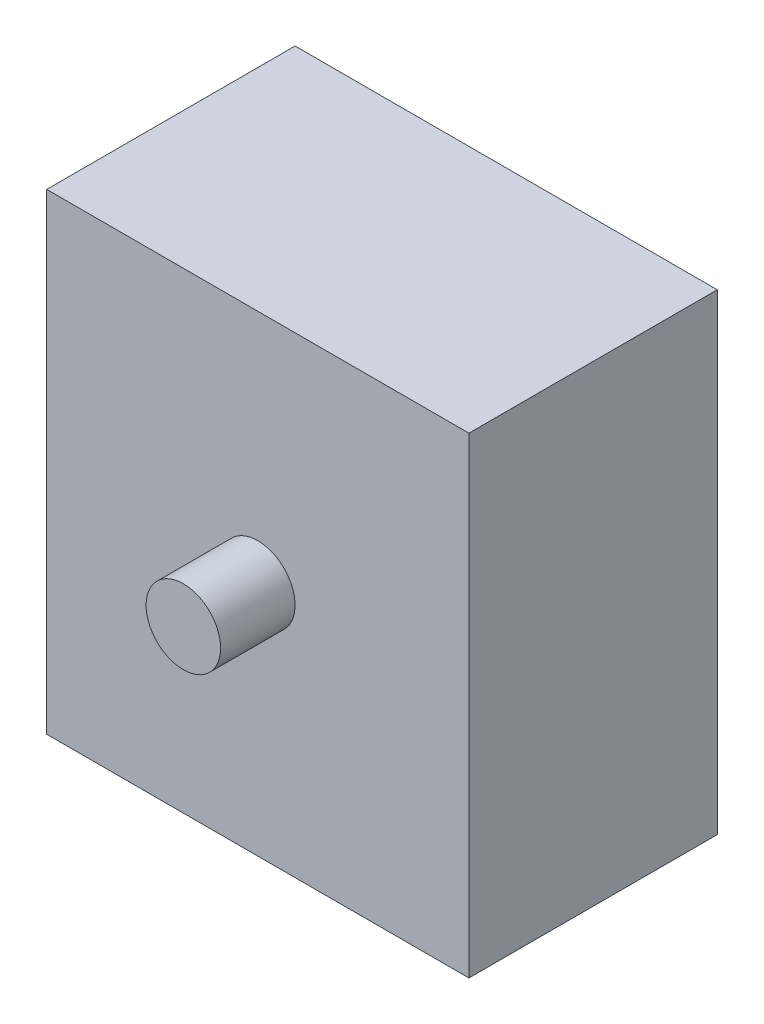
SolidWorks part; units mm, degrees
ref_plane "Top Plane" through (0, 0, 0) normal (0, 0, 1) x (1, 0, 0)
ref_plane "Front Plane" through (0, 0, 0) normal (0, 1, 0) x (1, 0, 0)
ref_plane "Right Plane" through (0, 0, 0) normal (1, 0, 0) x (0, 0, -1)
sketch "Sketch1" plane through (0, 0, 0) normal (0, 0, 1) x (1, 0, 0)
  line L0 (-8.5, 9.5) -> (8.5, -9.5) construction
  line L1 (-8.5, -9.5) -> (8.5, -9.5)
  line L2 (-8.5, -9.5) -> (-8.5, 9.5)
  line L3 (-8.5, 9.5) -> (8.5, 9.5)
  line L4 (8.5, -9.5) -> (8.5, 9.5)
  dimension "D1" = 17
  dimension "D2" = 19
extrude "Boss-Extrude1" add sketch "Sketch1" against normal blind 10 contours L3 L4 L1 L2
sketch "Sketch3" plane through (0, 0, 0) normal (0, 0, 1) x (1, 0, 0)
  circle A0 centre (0, 0) radius 1.5
  dimension "D1" = 3
extrude "Boss-Extrude2" add sketch "Sketch3" along normal blind 3
sketch "Sketch4" plane through (0, 0, 0) normal (0, 0, 1) x (1, 0, 0)
  line L0 (0, 0) -> (0, 1.5) construction
  line L1 (0, 9.5) -> (0, 4.5) construction
  line L2 (-8.5, 9.5) -> (8.5, 9.5) construction
  line L3 (0, 4.5) -> (-12.75, 4.5) construction
  line L4 (-8.5, -9.5) -> (-8.5, 9.5) construction
  line L5 (0, 0) -> (0, -4.5) construction
  line L6 (0, 13) -> (-12.75, 13) construction
  circle A0 centre (0, 0) radius 1.5 construction
  circle A1 centre (0, 0) radius 4.5 construction
  circle A2 centre (-12.75, 8.75) radius 4.25
  circle A3 centre (0, 0) radius 1.5
  circle A4 centre (0, 0) radius 13
  dimension "D1" = 5
  dimension "D2" = 9
  dimension "D3" = 8.5
  dimension "D7" = 3
  dimension "D8" = 26
  dimension "D4" = 12.75
  dimension "D5" = 4.5
  dimension "D6" = 4.5
